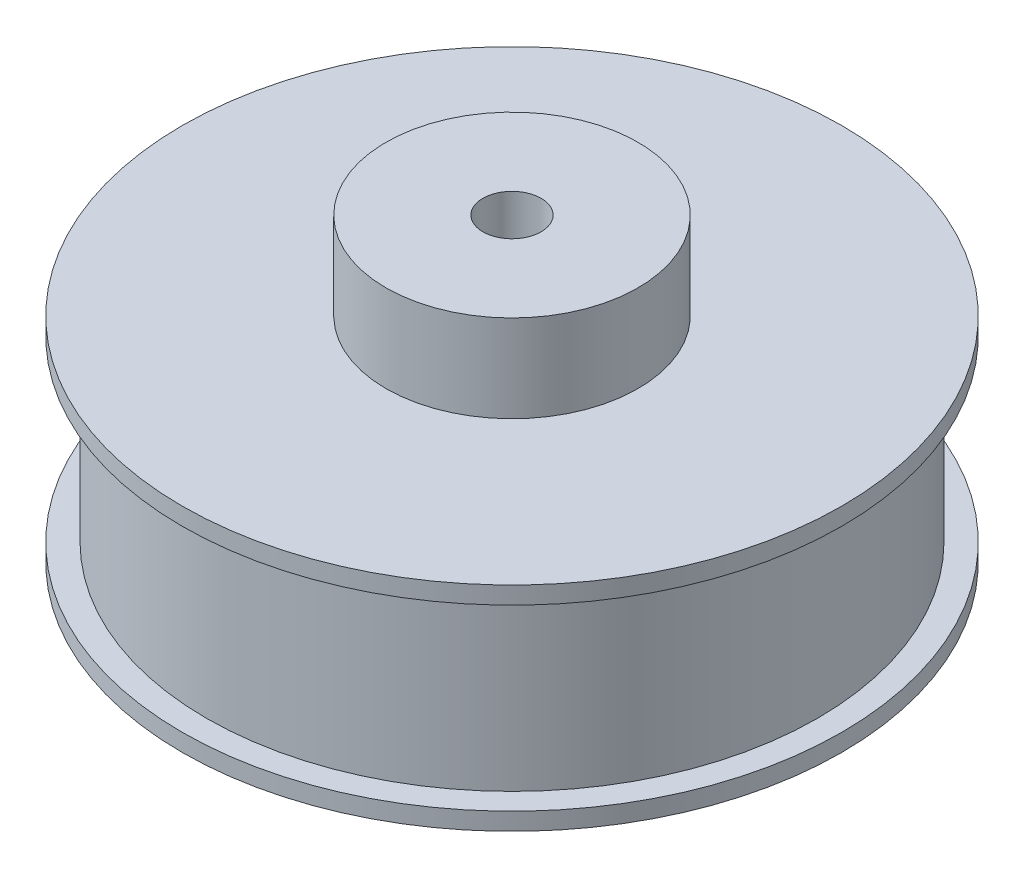
SolidWorks part; units mm, degrees
material "6061 Alloy"
ref_plane "Front Plane" through (0, 0, 0) normal (0, 0, 1) x (1, 0, 0)
ref_plane "Top Plane" through (0, 0, 0) normal (0, 1, 0) x (1, 0, 0)
ref_plane "Right Plane" through (0, 0, 0) normal (1, 0, 0) x (0, 0, -1)
sketch "Sketch1" plane through (0, 0, 0) normal (0, 0, 1) x (1, 0, 0)
  line L0 (0, 51.1748) -> (0, -42.6038) construction
  line L1 (0, -55) -> (0, 55) construction
  line L2 (3, 31) -> (13, 31)
  line L3 (13, 31) -> (13, 22)
  line L4 (13, 22) -> (34, 22)
  line L5 (34, 22) -> (34, 20.2)
  line L6 (55, 0) -> (-55, 0) construction
  line L7 (34, 0) -> (3, 0)
  line L8 (3, 0) -> (3, 31)
  line L9 (34, 20.2) -> (31.5, 20.2)
  line L10 (31.5, 20.2) -> (31.5, 1.8)
  line L11 (31.5, 1.8) -> (34, 1.8)
  line L12 (34, 1.8) -> (34, 0)
  dimension "D1" = 3
  dimension "D2" = 34
  dimension "D3" = 31.5
  dimension "D4" = 1.8
  dimension "D5" = 22
  dimension "D6" = 1.8
  dimension "D7" = 9
  dimension "D8" = 13
revolve "Revolve1" add sketch "Sketch1" angle 360 about L0
